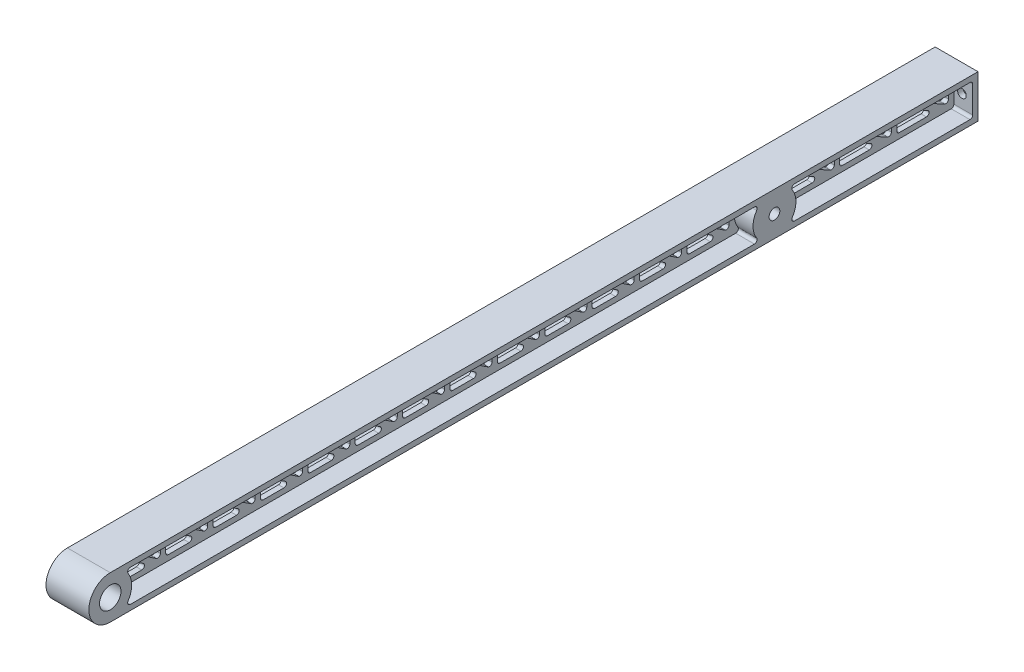
SolidWorks part; units mm, degrees
material "6061 Alloy"
ref_plane "Front Plane" through (0, 0, 0) normal (0, 0, 1) x (1, 0, 0)
ref_plane "Top Plane" through (0, 0, 0) normal (0, 1, 0) x (1, 0, 0)
ref_plane "Right Plane" through (0, 0, 0) normal (1, 0, 0) x (0, 0, -1)
sketch "Sketch1" plane through (0, 0, 0) normal (1, 0, 0) x (0, 0, -1)
  line L0 (0, 12.7) -> (514.35, 12.7)
  line L1 (0, -12.7) -> (514.35, -12.7)
  line L2 (514.35, 12.7) -> (514.35, 28.575) construction
  line L3 (514.35, 28.575) -> (520.7, 28.575) construction
  line L4 (520.7, 28.575) -> (520.7, -28.575) construction
  line L5 (520.7, -28.575) -> (514.35, -28.575) construction
  line L6 (514.35, -28.575) -> (514.35, -12.7) construction
  line L7 (514.35, 19.05) -> (558.8, 19.05) construction
  line L8 (558.8, 19.05) -> (558.8, -19.05) construction
  line L9 (558.8, -19.05) -> (514.35, -19.05) construction
  line L10 (514.35, 12.7) -> (514.35, -12.7)
  circle A0 centre (0, 0) radius 6.35
  arc A1 (0, -12.7) -> (0, 12.7) centre (0, 0) cw
  circle A4 centre (558.8, 0) radius 6.35 construction
  point P17 (520.7, 0)
  dimension "D1" = 12.7
  dimension "D2" = 12.7
  dimension "D6" = 38.1
  dimension "D3" = 6.35
  dimension "D4" = 57.15
  dimension "D7" = 558.8
  dimension "D8" = 25.4
  dimension "D9" = 38.1
extrude "Boss-Extrude1" add sketch "Sketch1" along normal blind 25.4
hole_wizard "1/4-20 Tapped Hole1" positions "Sketch3" profile "Sketch2" tap size "1/4-20" standard "ANSI Inch"
sketch "Sketch3" plane through (0, 0, -514.35) normal (0, 0, -1) x (-1, 0, 0)
  line L0 (0, 0) -> (-6.35, 0) construction
  line L2 (-6.35, 0) -> (-19.05, 0) construction
  line L3 (-19.05, 0) -> (-25.4, 0) construction
  line L5 (0, -12.7) -> (0, 12.7) construction
  line L6 (-25.4, -12.7) -> (-25.4, 12.7) construction
  point P13 (-6.35, 0)
  point P15 (-19.05, 0)
  dimension "D1" = 12.7
sketch "Sketch2" plane through (6.35, 0, -514.35) normal (1, 0, 0) x (0, 1, 0)
  line L0 (0, 0) -> (0, 18.0438)
  line L1 (0, 18.0438) -> (2.5527, 16.51)
  line L2 (2.5527, 16.51) -> (2.5527, 0)
  line L5 (2.5527, 0) -> (0, 0)
  line L10 (0, 18.0438) -> (-2.5527, 16.51) construction
  line L11 (0, -6.35) -> (0, 107.95) construction
  dimension "Tap Drill Dia." = 5.1054
  dimension "Tap Drill Depth" = 16.51
  dimension "Drill Angle" = 118
sketch "Sketch4" plane through (25.4, 0, 0) normal (1, 0, 0) x (0, 0, -1)
  line L0 (0, 0) -> (393.7, 0) construction
  circle A0 centre (393.7, 0) radius 3.175
  dimension "D1" = 6.35
  dimension "D2" = 393.7
extrude "Cut-Extrude1" cut sketch "Sketch4" against normal blind 38.1
sketch "Sketch19" plane through (25.4, 0, 0) normal (1, 0, 0) x (0, 0, -1)
  line L0 (0, 12.7) -> (0, 9.525)
  line L1 (0, -12.7) -> (0, -9.525)
  line L2 (0, 9.525) -> (514.35, 9.525)
  line L3 (514.35, -12.7) -> (514.35, 12.7) construction
  line L4 (514.35, -9.525) -> (0, -9.525)
  line L5 (514.35, 9.525) -> (511.175, 9.525)
  line L6 (511.175, 9.525) -> (511.175, -9.525)
  circle A0 centre (0, 0) radius 12.7
  circle A1 centre (393.7, 0) radius 12.7
  line M4 (514.35, -12.7) -> (514.35, 12.7)
  dimension "D1" = 25.4
  dimension "D2" = 25.4
  dimension "D3" = 3.175
  dimension "D4" = 3.175
  dimension "D5" = 3.175
extrude "Cut-Extrude2" cut sketch "Sketch19" against normal blind 11.1125 contours A1 L2 A0 L4 | A1 L4 L2 M4
sketch "Sketch21" plane through (14.2875, 0, 0) normal (1, 0, 0) x (0, 0, -1)
  line L0 (12.7, 0) -> (15.875, 0) construction
  line L1 (15.875, 6.35) -> (15.875, -6.35)
  line L2 (15.875, -6.35) -> (35.039, -6.35)
  line L3 (35.039, -6.35) -> (15.875, 6.35)
  line L4 (21.6225, 6.35) -> (40.7865, -6.35)
  line L5 (21.6225, 6.35) -> (40.7865, 6.35)
  line L6 (40.7865, 6.35) -> (40.7865, -6.35)
  line L7 (29.4506, -2.6466) -> (31.2045, 0) construction
  line L8 (43.9615, 6.35) -> (43.9615, -6.35)
  line L9 (43.9615, -6.35) -> (63.1255, -6.35)
  line L10 (63.1255, -6.35) -> (43.9615, 6.35)
  line L11 (49.7091, 6.35) -> (68.8731, -6.35)
  line L12 (49.7091, 6.35) -> (68.8731, 6.35)
  line L13 (68.8731, 6.35) -> (68.8731, -6.35)
  line L14 (40.7865, 0) -> (43.9615, 0) construction
  line L15 (57.5372, -2.6466) -> (59.2911, 0) construction
  line L16 (72.0481, 6.35) -> (72.0481, -6.35)
  line L17 (72.0481, -6.35) -> (91.2121, -6.35)
  line L18 (91.2121, -6.35) -> (72.0481, 6.35)
  line L19 (77.7956, 6.35) -> (96.9596, -6.35)
  line L20 (77.7956, 6.35) -> (96.9596, 6.35)
  line L21 (96.9596, 6.35) -> (96.9596, -6.35)
  line L22 (68.8731, 0) -> (72.0481, 0) construction
  line L23 (85.6237, -2.6466) -> (87.3776, 0) construction
  line L24 (100.1346, 6.35) -> (100.1346, -6.35)
  line L25 (100.1346, -6.35) -> (119.2986, -6.35)
  line L26 (119.2986, -6.35) -> (100.1346, 6.35)
  line L27 (105.8822, 6.35) -> (125.0462, -6.35)
  line L28 (105.8822, 6.35) -> (125.0462, 6.35)
  line L29 (125.0462, 6.35) -> (125.0462, -6.35)
  line L30 (96.9596, 0) -> (100.1346, 0) construction
  line L31 (113.7103, -2.6466) -> (115.4642, 0) construction
  line L32 (128.2212, 6.35) -> (128.2212, -6.35)
  line L33 (128.2212, -6.35) -> (147.3851, -6.35)
  line L34 (147.3851, -6.35) -> (128.2212, 6.35)
  line L35 (133.9687, 6.35) -> (153.1327, -6.35)
  line L36 (133.9687, 6.35) -> (153.1327, 6.35)
  line L37 (153.1327, 6.35) -> (153.1327, -6.35)
  line L38 (125.0462, 0) -> (128.2212, 0) construction
  line L39 (141.7968, -2.6466) -> (143.5507, 0) construction
  line L40 (156.3077, 6.35) -> (156.3077, -6.35)
  line L41 (156.3077, -6.35) -> (175.4717, -6.35)
  line L42 (175.4717, -6.35) -> (156.3077, 6.35)
  line L43 (162.0552, 6.35) -> (181.2192, -6.35)
  line L44 (162.0552, 6.35) -> (181.2192, 6.35)
  line L45 (181.2192, 6.35) -> (181.2192, -6.35)
  line L46 (153.1327, 0) -> (156.3077, 0) construction
  line L47 (169.8833, -2.6466) -> (171.6372, 0) construction
  line L48 (184.3942, 6.35) -> (184.3942, -6.35)
  line L49 (184.3942, -6.35) -> (203.5582, -6.35)
  line L50 (203.5582, -6.35) -> (184.3942, 6.35)
  line L51 (190.1418, 6.35) -> (209.3058, -6.35)
  line L52 (190.1418, 6.35) -> (209.3058, 6.35)
  line L53 (209.3058, 6.35) -> (209.3058, -6.35)
  line L54 (181.2192, 0) -> (184.3942, 0) construction
  line L55 (197.9699, -2.6466) -> (199.7238, 0) construction
  line L56 (212.4808, 6.35) -> (212.4808, -6.35)
  line L57 (212.4808, -6.35) -> (231.6448, -6.35)
  line L58 (231.6448, -6.35) -> (212.4808, 6.35)
  line L59 (218.2283, 6.35) -> (237.3923, -6.35)
  line L60 (218.2283, 6.35) -> (237.3923, 6.35)
  line L61 (237.3923, 6.35) -> (237.3923, -6.35)
  line L62 (209.3058, 0) -> (212.4808, 0) construction
  line L63 (226.0564, -2.6466) -> (227.8103, 0) construction
  line L64 (240.5673, 6.35) -> (240.5673, -6.35)
  line L65 (240.5673, -6.35) -> (259.7313, -6.35)
  line L66 (259.7313, -6.35) -> (240.5673, 6.35)
  line L67 (246.3149, 6.35) -> (265.4788, -6.35)
  line L68 (246.3149, 6.35) -> (265.4788, 6.35)
  line L69 (265.4788, 6.35) -> (265.4788, -6.35)
  line L70 (237.3923, 0) -> (240.5673, 0) construction
  line L71 (254.1429, -2.6466) -> (255.8969, 0) construction
  line L72 (268.6538, 6.35) -> (268.6538, -6.35)
  line L73 (268.6538, -6.35) -> (287.8178, -6.35)
  line L74 (287.8178, -6.35) -> (268.6538, 6.35)
  line L75 (274.4014, 6.35) -> (293.5654, -6.35)
  line L76 (274.4014, 6.35) -> (293.5654, 6.35)
  line L77 (293.5654, 6.35) -> (293.5654, -6.35)
  line L78 (265.4788, 0) -> (268.6538, 0) construction
  line L79 (282.2295, -2.6466) -> (283.9834, 0) construction
  line L80 (296.7404, 6.35) -> (296.7404, -6.35)
  line L81 (296.7404, -6.35) -> (315.9044, -6.35)
  line L82 (315.9044, -6.35) -> (296.7404, 6.35)
  line L83 (302.4879, 6.35) -> (321.6519, -6.35)
  line L84 (302.4879, 6.35) -> (321.6519, 6.35)
  line L85 (321.6519, 6.35) -> (321.6519, -6.35)
  line L86 (293.5654, 0) -> (296.7404, 0) construction
  line L87 (310.316, -2.6466) -> (312.0699, 0) construction
  line L88 (324.8269, 6.35) -> (324.8269, -6.35)
  line L89 (324.8269, -6.35) -> (343.9909, -6.35)
  line L90 (343.9909, -6.35) -> (324.8269, 6.35)
  line L91 (330.5745, 6.35) -> (349.7385, -6.35)
  line L92 (330.5745, 6.35) -> (349.7385, 6.35)
  line L93 (349.7385, 6.35) -> (349.7385, -6.35)
  line L94 (321.6519, 0) -> (324.8269, 0) construction
  line L95 (338.4026, -2.6466) -> (340.1565, 0) construction
  line L96 (352.9135, 6.35) -> (352.9135, -6.35)
  line L97 (352.9135, -6.35) -> (372.0775, -6.35)
  line L98 (372.0775, -6.35) -> (352.9135, 6.35)
  line L99 (358.661, 6.35) -> (377.825, -6.35)
  line L100 (358.661, 6.35) -> (377.825, 6.35)
  line L101 (377.825, 6.35) -> (377.825, -6.35)
  line L102 (349.7385, 0) -> (352.9135, 0) construction
  line L103 (366.4891, -2.6466) -> (368.243, 0) construction
  line L104 (15.875, 6.35) -> (43.9615, 6.35) construction
  line L105 (406.4, 0) -> (409.575, 0)
  line L106 (409.575, 6.35) -> (409.575, -6.35)
  line L107 (409.575, -6.35) -> (433.4959, -6.35)
  line L108 (433.4959, -6.35) -> (409.575, 6.35)
  line L109 (416.3458, 6.35) -> (440.2667, -6.35)
  line L110 (440.2667, -6.35) -> (440.2667, 6.35)
  line L111 (440.2667, 6.35) -> (416.3458, 6.35)
  line L112 (421.5354, 0) -> (423.0243, 2.8043)
  line L113 (440.2667, 0) -> (443.4417, 0)
  line L114 (443.4417, 6.35) -> (443.4417, -6.35)
  line L115 (443.4417, -6.35) -> (467.3625, -6.35)
  line L116 (467.3625, -6.35) -> (443.4417, 6.35)
  line L117 (450.2125, 6.35) -> (474.1333, -6.35)
  line L118 (474.1333, -6.35) -> (474.1333, 6.35)
  line L119 (474.1333, 6.35) -> (450.2125, 6.35)
  line L120 (455.4021, 0) -> (456.8909, 2.8043)
  line L121 (474.1333, 0) -> (477.3083, 0)
  line L122 (477.3083, 6.35) -> (477.3083, -6.35)
  line L123 (477.3083, -6.35) -> (501.2292, -6.35)
  line L124 (501.2292, -6.35) -> (477.3083, 6.35)
  line L125 (484.0791, 6.35) -> (508, -6.35)
  line L126 (508, -6.35) -> (508, 6.35)
  line L127 (508, 6.35) -> (484.0791, 6.35)
  line L128 (489.2688, 0) -> (490.7576, 2.8043)
  line L130 (511.175, 0) -> (508, 0)
  line L131 (511.175, 9.525) -> (511.175, -9.525) construction
  arc A0 (8.4003, -9.525) -> (8.4003, 9.525) centre (0, 0) ccw construction
  arc A1 (385.2997, 9.525) -> (385.2997, -9.525) centre (393.7, 0) ccw construction
  arc A2 (402.1003, -9.525) -> (402.1003, 9.525) centre (393.7, 0) ccw construction
  point P14 (381, 0)
  dimension "D1" = 3.175
  dimension "D2" = 12.7
  dimension "D3" = 3.175
  dimension "D4" = 13
  dimension "D5" = 3.175
  dimension "D6" = 3.175
  dimension "D7" = 12.7
  dimension "D8" = 3.175
  dimension "D11" = 3.175
  dimension "D12" = 3.175
  dimension "D13" = 3.175
  dimension "D9" = 3
extrude "Cut-Extrude3" cut sketch "Sketch21" against normal through all contours L2 L3 L1 | L6 L5 L4 | L9 L10 L8 | L13 L12 L11 | L17 L18 L16 | L21 L20 L19 | L25 L26 L24 | L29 L28 L27 | L33 L34 L32 | L37 L36 L35 | L41 L42 L40 | L45 L44 L43 | L49 L50 L48 | L53 L52 L51 | L57 L58 L56 | L61 L60 L59 | L65 L66 L64 | L69 L68 L67 | L73 L74 L72 | L77 L76 L75 | L81 L82 L80 | L85 L84 L83 | L89 L90 L88 | L93 L92 L91 | L97 L98 L96 | L101 L100 L99 | L107 L108 L106 | L110 L111 L109 | L115 L116 L114 | L118 L119 L117 | L123 L124 L122 | L126 L127 L125
ref_plane "half arm" through (12.7, 0, 0) normal (-1, 0, 0) x (0, 0, 1)
mirror "Mirror2" about plane through (12.7, 0, 0) normal (-1, 0, 0) of "Cut-Extrude2"
fillet "Fillet1" radius 1.5875 92 edges at (12.7, 6.35, -358.661) (12.7, 6.35, -377.825) (12.7, -6.35, -377.825) (12.7, -6.35, -352.9135) (12.7, 6.35, -352.9135) (12.7, 6.35, -321.6519) (12.7, -6.35, -321.6519) (12.7, -6.35, -296.7404) (12.7, 6.35, -296.7404) (12.7, -6.35, -315.9044) (12.7, 6.35, -246.3149) (12.7, 6.35, -265.4788) (12.7, -6.35, -265.4788) (12.7, 6.35, -240.5673) (12.7, 6.35, -190.1418) (12.7, 6.35, -209.3058) (12.7, -6.35, -209.3058) (12.7, -6.35, -184.3942) (12.7, 6.35, -184.3942) (12.7, -6.35, -203.5582) (12.7, 6.35, -133.9687) (12.7, 6.35, -153.1327) (12.7, -6.35, -153.1327) (12.7, -6.35, -128.2212) (12.7, 6.35, -128.2212) (12.7, -6.35, -147.3851) (12.7, 6.35, -77.7956) (12.7, 6.35, -96.9596) (12.7, -6.35, -96.9596) (12.7, -6.35, -91.2121) (12.7, 6.35, -40.7865) (12.7, -6.35, -40.7865) (12.7, 6.35, -15.875) (12.7, -6.35, -35.039) (12.7, -6.35, -43.9615) (12.7, 6.35, -43.9615) (12.7, -6.35, -63.1255) (12.7, 6.35, -49.7091) (12.7, 6.35, -68.8731) (12.7, -6.35, -100.1346) (12.7, 6.35, -100.1346) (12.7, -6.35, -119.2986) (12.7, 6.35, -105.8822) (12.7, 6.35, -125.0462) (12.7, -6.35, -125.0462) (12.7, -6.35, -156.3077) (12.7, 6.35, -156.3077) (12.7, -6.35, -175.4717) (12.7, 6.35, -162.0552) (12.7, 6.35, -181.2192) (12.7, -6.35, -212.4808) (12.7, 6.35, -212.4808) (12.7, -6.35, -231.6448) (12.7, 6.35, -218.2283) (12.7, 6.35, -237.3923) (12.7, -6.35, -237.3923) (12.7, -6.35, -268.6538) (12.7, -6.35, -287.8178) (12.7, 6.35, -274.4014) (12.7, 6.35, -293.5654) (12.7, -6.35, -293.5654) (12.7, -6.35, -324.8269) (12.7, 6.35, -324.8269) (12.7, -6.35, -343.9909) (12.7, 6.35, -349.7385) (12.7, -6.35, -349.7385) (12.7, -6.35, -433.4959) (12.7, -6.35, -440.2667) (12.7, 6.35, -416.3458) (12.7, 6.35, -443.4417) (12.7, -6.35, -474.1333) (12.7, 6.35, -474.1333) (12.7, -6.35, -477.3083) (12.7, 6.35, -477.3083) (12.7, -6.35, -501.2292) (12.7, -6.35, -508) (12.7, 6.35, -484.0791) (12.7, 6.35, -508) (12.7, -6.35, -15.875) (19.8438, -9.525, -402.1003) (19.8438, -9.525, -511.175) (19.8438, 9.525, -511.175) (19.8438, 9.525, -402.1003) (19.8438, 9.525, -385.2997) (19.8438, 9.525, -8.4003) (19.8438, -9.525, -8.4003) (5.5562, -9.525, -8.4003) (5.5562, 9.525, -8.4003) (5.5562, -9.525, -385.2997) (5.5562, 9.525, -385.2997) (5.5562, 9.525, -402.1003) (5.5562, 9.525, -511.175)
